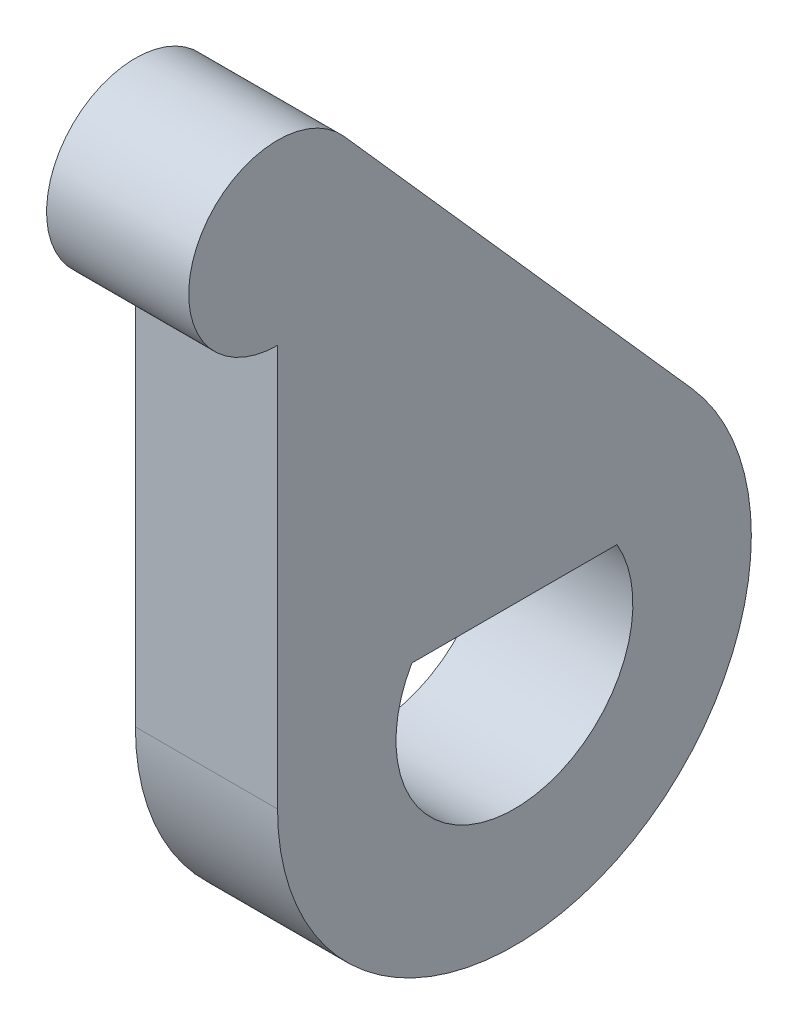
SolidWorks part; units mm, degrees
ref_plane "Front Plane" through (0, 0, 0) normal (0, 0, 1) x (1, 0, 0)
ref_plane "Top Plane" through (0, 0, 0) normal (0, 1, 0) x (1, 0, 0)
ref_plane "Right Plane" through (0, 0, 0) normal (1, 0, 0) x (0, 0, -1)
sketch "Sketch1" plane through (0, 0, 0) normal (1, 0, 0) x (0, 0, -1)
  line L0 (-5.4991, 3.1753) -> (5.4991, 3.1753)
  line L1 (-12.7, 0) -> (-12.7, 21.5245)
  line L2 (-9.1366, 29.4467) -> (9.5025, 8.4257)
  arc A0 (-5.4991, 3.1753) -> (5.4991, 3.1753) centre (0, 0) ccw
  arc A1 (-12.7, 0) -> (9.5025, 8.4257) centre (0, 0) ccw
  arc A2 (-9.1366, 29.4467) -> (-12.7, 21.5245) centre (-12.7, 26.287) ccw
  dimension "D1" = 12.7
  dimension "D2" = 25.4
  dimension "D3" = 9.525
  dimension "D4" = 10.9982
  dimension "D5" = 9.5025
extrude "Boss-Extrude1" add sketch "Sketch1" along normal mid plane 7.62
